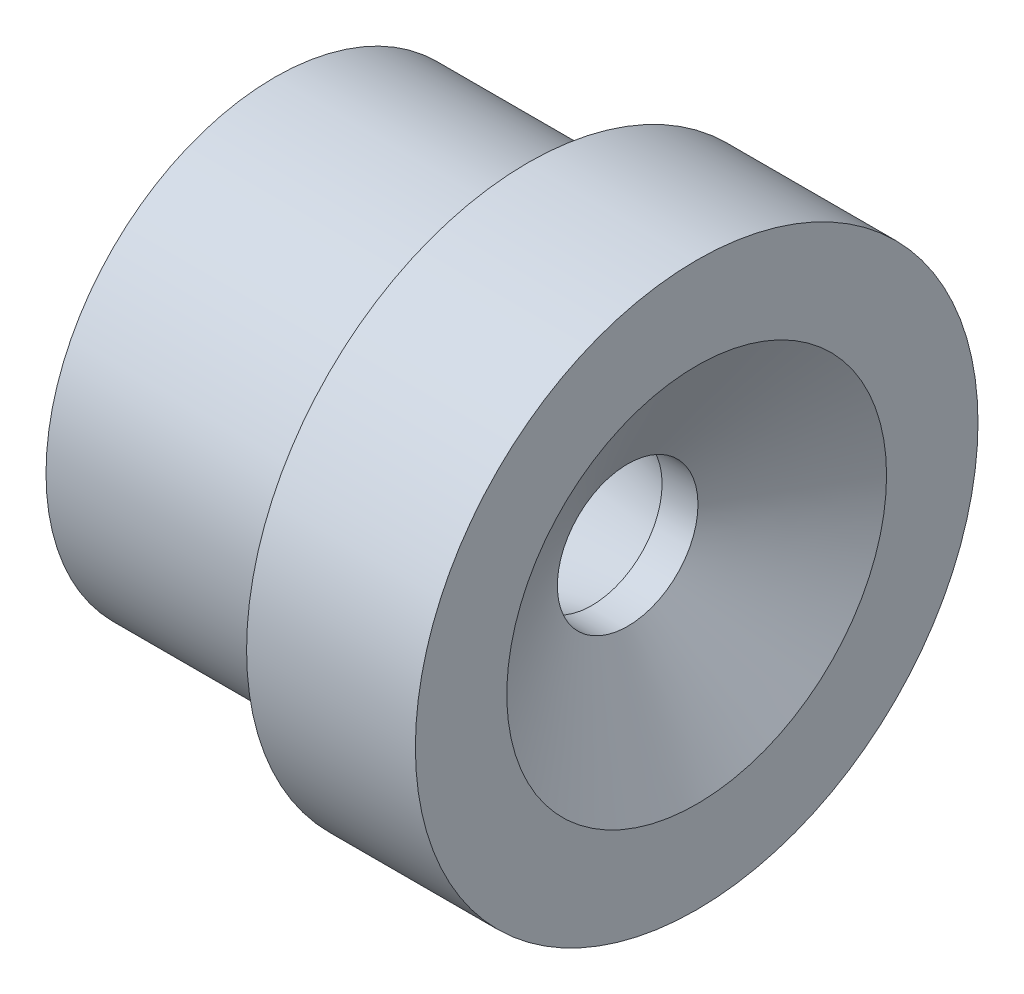
SolidWorks part; units mm, degrees
material "C (Graphite)"
ref_plane "Front Plane" through (0, 0, 0) normal (0, 0, 1) x (1, 0, 0)
ref_plane "Top Plane" through (0, 0, 0) normal (0, 1, 0) x (1, 0, 0)
ref_plane "Right Plane" through (0, 0, 0) normal (1, 0, 0) x (0, 0, -1)
sketch "Sketch1" plane through (0, 0, 0) normal (0, 1, 0) x (1, 0, 0)
  line L0 (0, 0) -> (0, 4.1275)
  line L1 (0, 4.1275) -> (-3.1162, 9.525)
  line L2 (-3.1162, 9.525) -> (-4.7368, 9.525)
  line L3 (-4.7368, 9.525) -> (-19.05, 5.6898)
  line L4 (-19.05, 5.6898) -> (-19.05, 2.3749)
  line L5 (-19.05, 2.3749) -> (-7.62, 2.3749)
  line L6 (-7.62, 2.3749) -> (-7.62, 0)
  line L9 (-7.62, 0) -> (0, 0)
  line L10 (5.1187, 12.7) -> (-11.0703, 12.7) construction
  dimension "D1" = 25.4
  dimension "D2" = 6.35
  dimension "D3" = 60
  dimension "D4" = 15
  dimension "D5" = 17.145
  dimension "D6" = 1.6205
  dimension "D7" = 7.62
  dimension "D8" = 19.05
  dimension "D9" = 20.6502
revolve "Revolve1" add sketch "Sketch1" angle 360 about L10
